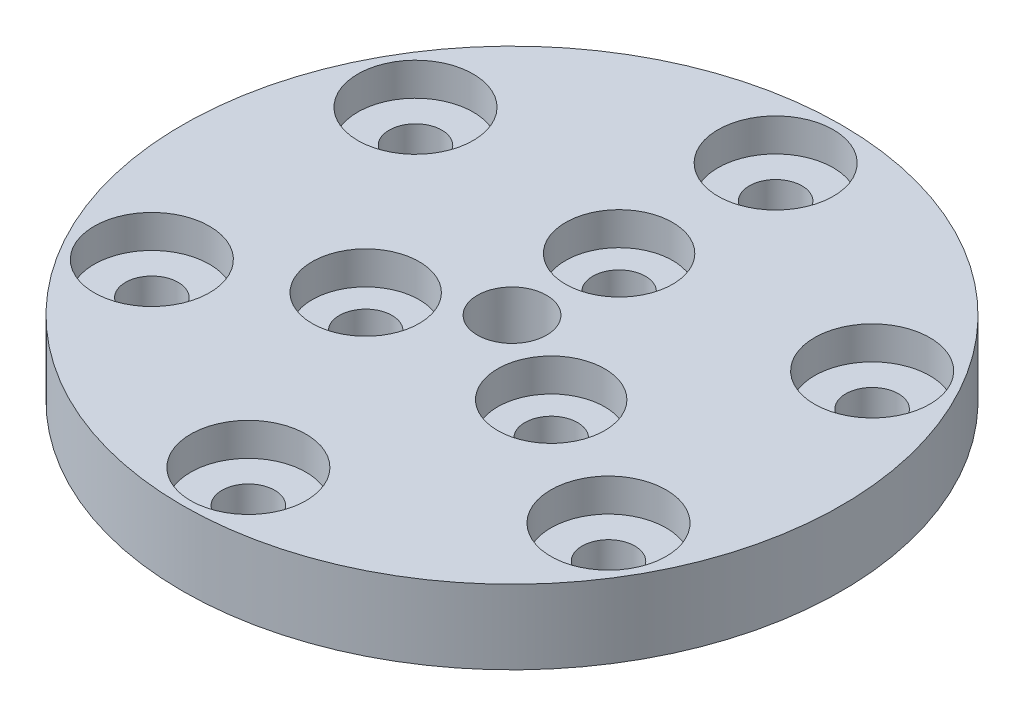
SolidWorks part; units mm, degrees
ref_plane "Front Plane" through (0, 0, 0) normal (0, 0, 1) x (1, 0, 0)
ref_plane "Top Plane" through (0, 0, 0) normal (0, 1, 0) x (1, 0, 0)
ref_plane "Right Plane" through (0, 0, 0) normal (1, 0, 0) x (0, 0, -1)
sketch "Sketch1" plane through (0, 0, 0) normal (0, 1, 0) x (1, 0, 0)
  circle A0 centre (0, 0) radius 20
  circle A1 centre (0, 0) radius 2.1
  dimension "D1" = 4.2
  dimension "D2" = 40
extrude "Boss-Extrude1" add sketch "Sketch1" along normal up to surface (4.5 mm away)
sketch "Sketch2" plane through (0, 0, 0) normal (0, -1, 0) x (1, 0, 0)
  line L0 (0, 0) -> (0, 16) construction
  circle A0 centre (0, 16) radius 1.6
  dimension "D1" = 3.2
  dimension "D2" = 16
extrude "Cut-Extrude1" cut sketch "Sketch2" against normal through all
sketch "Sketch5" plane through (0, 4.5, 0) normal (0, 1, 0) x (1, 0, 0)
  circle A4 centre (0, -16) radius 3.5
  circle A5 centre (0, -16) radius 1.6 construction
  circle A6 centre (0, -16) radius 1.6 construction
  dimension "D1" = 7
extrude "Cut-Extrude4" cut sketch "Sketch5" against normal blind 2
pattern_circular "CirPattern1" count 6 over 360 about axis through (0, 0, 0) along (0, 1, 0) of "Cut-Extrude1", "Cut-Extrude4"
sketch "Sketch3" plane through (0, 4.5, 0) normal (0, 1, 0) x (1, 0, 0)
  line L0 (0, 0) -> (0, 6.5) construction
  circle A0 centre (0, 6.5) radius 1.6
  dimension "D1" = 3.2
  dimension "D2" = 6.5
extrude "Cut-Extrude2" cut sketch "Sketch3" against normal through all
sketch "Sketch4" plane through (0, 4.5, 0) normal (0, 1, 0) x (1, 0, 0)
  circle A0 centre (0, 6.5) radius 3.25
  dimension "D1" = 6.5
extrude "Cut-Extrude3" cut sketch "Sketch4" against normal blind 2
pattern_circular "CirPattern2" count 3 over 360 about axis through (0, 0, 0) along (0, 1, 0) of "Cut-Extrude2", "Cut-Extrude3"
